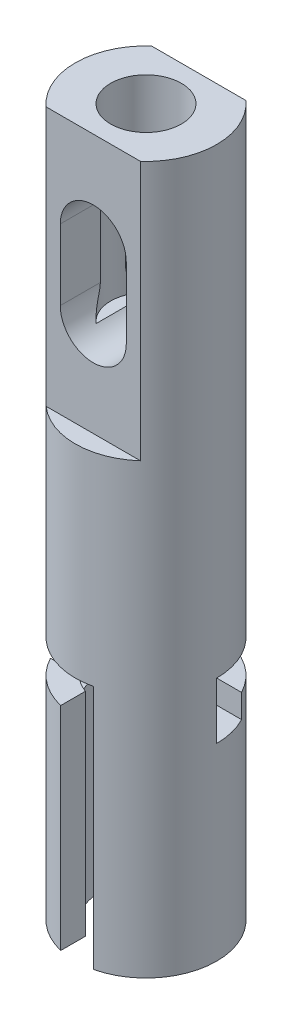
SolidWorks part; units mm, degrees
ref_plane "Front Plane" through (0, 0, 0) normal (0, 0, 1) x (1, 0, 0)
ref_plane "Top Plane" through (0, 0, 0) normal (0, 1, 0) x (1, 0, 0)
ref_plane "Right Plane" through (0, 0, 0) normal (1, 0, 0) x (0, 0, -1)
sketch "Sketch1" plane through (0, 0, 0) normal (0, 1, 0) x (1, 0, 0)
  circle A0 centre (0, 0) radius 15
  dimension "D1" = 30
extrude "Boss-Extrude1" add sketch "Sketch1" along normal mid plane 150
sketch "Sketch2" plane through (0, -75, 0) normal (0, -1, 0) x (1, 0, 0)
  line L0 (0, 15) -> (0, -15) construction
  line L1 (3.5, 15) -> (3.5, -15)
  line L2 (-3.5, 15) -> (-3.5, -15)
  circle A0 centre (0, 0) radius 15 construction
  arc A1 (3.5, 15) -> (-3.5, 15) centre (0, 15) ccw
  arc A2 (-3.5, -15) -> (3.5, -15) centre (0, -15) ccw
  point P6 (0, 0)
  dimension "D1" = 3.5
extrude "Cut-Extrude1" cut sketch "Sketch2" against normal blind 52
ref_plane "Plane1" through (0, -26.5, 0) normal (0, 1, 0) x (1, 0, 0)
sketch "Sketch3" plane through (0, -26.5, 0) normal (0, 1, 0) x (1, 0, 0)
  line L1 (-14.9801, 0) -> (-15.3281, -9.9939)
  line L2 (0, -7) -> (-0.348, -16.9939)
  line L3 (15, 0) -> (0, 7)
  line L4 (15, 0) -> (15.348, 9.9939)
  line L5 (0, 7) -> (0.348, 16.9939)
  line L6 (15.348, 9.9939) -> (0.348, 16.9939)
  line L7 (-15.3281, -9.9939) -> (-0.348, -16.9939)
  line L8 (-14.9801, 0) -> (0, -7)
  circle A0 centre (0, 0) radius 15 construction
  point P0 (0, -7)
  point P5 (-14.9801, 0)
  dimension "D1" = 7
  dimension "D2" = 7
  dimension "D3" = 10
extrude "Cut-Extrude2" cut sketch "Sketch3" against normal mid plane 7
ref_plane "Plane2" through (0, -35, 0) normal (0, 1, 0) x (1, 0, 0)
sketch "Sketch9" plane through (0, -75, 0) normal (0, -1, 0) x (1, 0, 0)
  circle A0 centre (0, 0) radius 10
  dimension "D1" = 20
extrude "Cut-Extrude12" cut sketch "Sketch9" against normal blind 70
ref_plane "Plane5" through (15, 0, 0) normal (1, 0, 0) x (0, 0, -1)
sketch "Sketch17" plane through (15, 0, 0) normal (1, 0, 0) x (0, 0, -1)
  line L0 (0, -23) -> (0, -35)
  line L1 (0, -23) -> (7, -23)
  line L2 (0, -35) -> (7, -35)
  line L3 (7, -23) -> (7, -35)
  line L4 (16.5, -35) -> (-16.5, -35) construction
  dimension "D1" = 7
extrude "Cut-Extrude19" cut sketch "Sketch17" against normal blind 15
ref_plane "Plane6" through (-15, 0, 0) normal (1, 0, 0) x (0, 0, -1)
ref_plane "Plane7" through (-15, 0, 0) normal (-1, 0, 0) x (0, 0, 1)
sketch "Sketch19" plane through (-15, 0, 0) normal (-1, 0, 0) x (0, 0, 1)
  line L0 (0, -23) -> (0, -35)
  line L1 (0, -23) -> (7, -23)
  line L2 (0, -35) -> (7, -35)
  line L3 (7, -23) -> (7, -35)
  line L4 (2.4722, -23) -> (0, -23) construction
  line L5 (16.5, -35) -> (-16.5, -35) construction
  dimension "D1" = 7
extrude "Cut-Extrude20" cut sketch "Sketch19" against normal blind 15
sketch "Sketch20" plane through (0, 75, 0) normal (0, 1, 0) x (1, 0, 0)
  circle A0 centre (0, 0) radius 7.5
  dimension "D1" = 15
extrude "Cut-Extrude21" cut sketch "Sketch20" against normal blind 40
sketch "Sketch21" plane through (0, 75, 0) normal (0, 1, 0) x (1, 0, 0)
  line L1 (-10, 11.1803) -> (10, 11.1803)
  line L2 (-10, 11.1803) -> (-10, 18.8197)
  line L3 (-10, 18.8197) -> (10, 18.8197)
  line L4 (10, 11.1803) -> (10, 18.8197)
  line L5 (-10, 11.1803) -> (10, 18.8197) construction
  line L6 (-10, 18.8197) -> (10, 11.1803) construction
  line L7 (10, -11.1803) -> (10, -18.8197)
  line L8 (-10, -11.1803) -> (-10, -18.8197)
  line L9 (-10, -18.8197) -> (10, -18.8197)
  line L10 (-10, -18.8197) -> (10, -11.1803) construction
  line L11 (-10, -11.1803) -> (10, -18.8197) construction
  line L12 (-10, -11.1803) -> (10, -11.1803)
  circle A0 centre (0, 0) radius 15 construction
  point P0 (0, 15)
  point P12 (0, 0)
  dimension "D1" = 20
extrude "Cut-Extrude25" cut sketch "Sketch21" against normal blind 55 and the other way through all
sketch "Sketch23" plane through (0, 0, -11.1803) normal (0, 0, -1) x (-1, 0, 0)
  line L0 (-10, 75) -> (10, 75) construction
  line L1 (0, 55) -> (0, 40) construction
  line L3 (7, 55) -> (7, 40)
  line L4 (-7, 55) -> (-7, 40)
  arc A0 (7, 55) -> (-7, 55) centre (0, 55) ccw
  arc A1 (-7, 40) -> (7, 40) centre (0, 40) ccw
  point P1 (0, 47.5)
  point P8 (0, 47.5)
  dimension "D2" = 7
  dimension "D1" = 27.5
  dimension "D3" = 15
extrude "Cut-Extrude27" cut sketch "Sketch23" against normal through all both and the other way through all
